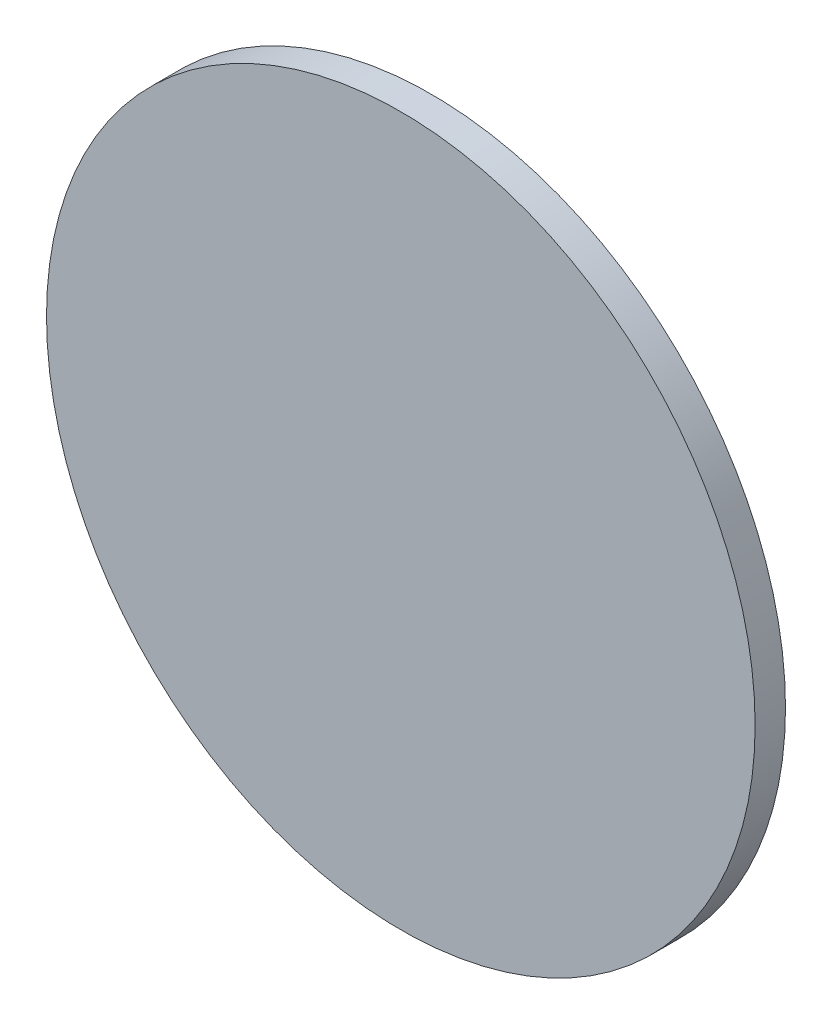
SolidWorks part; units mm, degrees
ref_plane "Спереди" through (0, 0, 0) normal (0, 0, 1) x (1, 0, 0)
ref_plane "Сверху" through (0, 0, 0) normal (0, 1, 0) x (1, 0, 0)
ref_plane "Справа" through (0, 0, 0) normal (1, 0, 0) x (0, 0, -1)
sketch "Sketch1" plane through (0, 0, 0) normal (0, 0, 1) x (1, 0, 0)
  circle A0 centre (0, 0) radius 17.5
extrude "Boss-Extrude1" add sketch "Sketch1" along normal blind 1.5 contours A0
